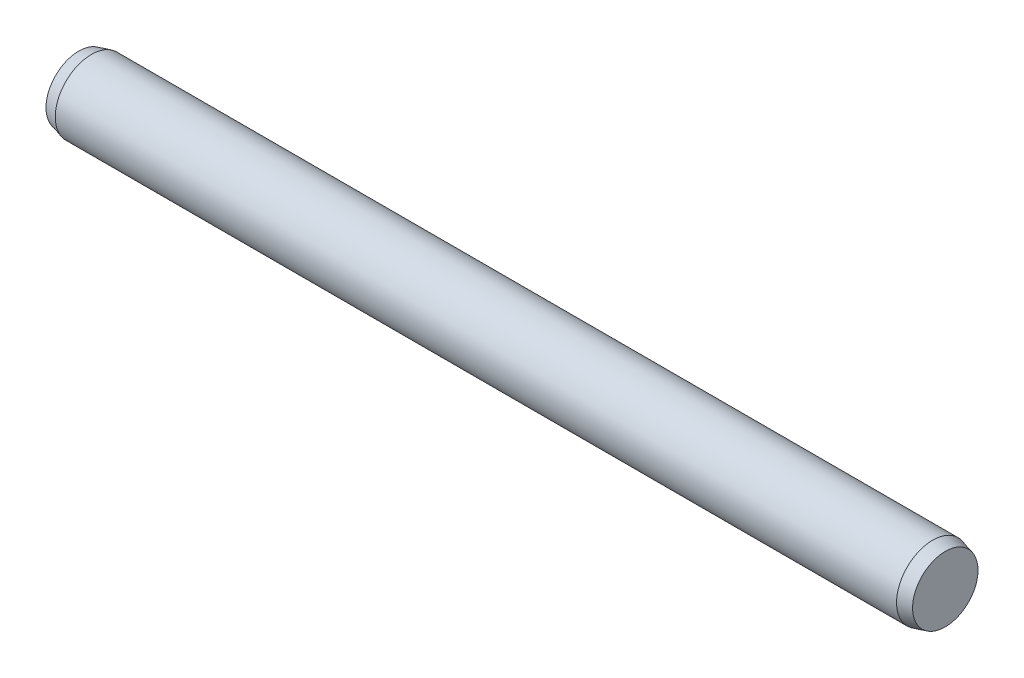
SolidWorks part; units mm, degrees
ref_plane "Front Plane" through (0, 0, 0) normal (0, 0, 1) x (1, 0, 0)
ref_plane "Top Plane" through (0, 0, 0) normal (0, 1, 0) x (1, 0, 0)
ref_plane "Right Plane" through (0, 0, 0) normal (1, 0, 0) x (0, 0, -1)
sketch "Sketch1" plane through (0, 0, 0) normal (0, 0, 1) x (1, 0, 0)
  line L0 (-11.65, 0) -> (11.65, 0) construction
  line L1 (11.65, 1) -> (11.65, -1) construction
  line L2 (-11.65, 1) -> (-11.65, -1) construction
  line L3 (12, 1) -> (12, -1) construction
  line L4 (-12, 1) -> (-12, -1) construction
  line L5 (-11.65, 0) -> (-12, 0) construction
  line L6 (11.65, 0) -> (12, 0) construction
  dimension "D1" = 0.35
  dimension "Dia" = 2
  dimension "Length" = 24
  dimension "C" = 0.35
sketch "Sketch2" plane through (0, 0, 0) normal (1, 0, 0) x (0, 0, -1)
  circle A0 centre (0, 0) radius 1
extrude "Extrude1" add sketch "Sketch2" against normal up to vertex (11.65 mm away) and the other way up to vertex (11.65 mm away) up to point (-11.65, 1, 0) other way up to point (11.65, 1, 0)
sketch "Sketch3" plane through (11.65, 0, 0) normal (1, 0, 0) x (0, 0, -1)
  circle A1 centre (0, 0) radius 1
  circle A2 centre (0, 0) radius 1
  dimension "D1" = 0
extrude "Extrude2" add sketch "Sketch3" along normal up to vertex (0.35 mm away) draft 15 up to point (12, 0, 0)
sketch "Sketch4" plane through (-11.65, 0, 0) normal (-1, 0, 0) x (0, 0, 1)
  circle A1 centre (0, 0) radius 1
  circle A2 centre (0, 0) radius 1
  dimension "D1" = 0
extrude "Extrude3" add sketch "Sketch4" along normal up to vertex (0.35 mm away) draft 15 up to point (-12, 0, 0)
equation "\"D1@Sketch1\" = \"C@Sketch1\""
